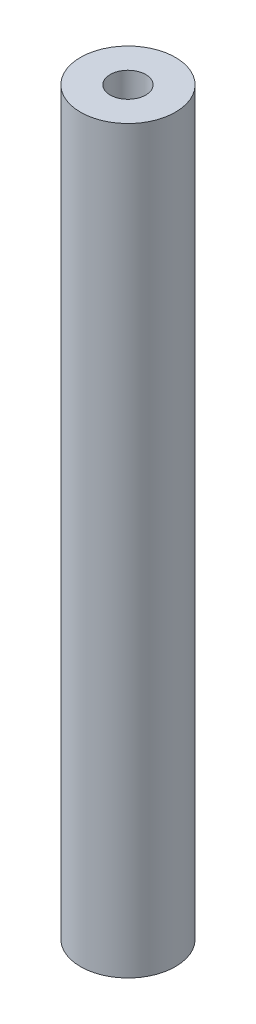
SolidWorks part; units mm, degrees
material "Aleación 6061"
ref_plane "Alzado" through (0, 0, 0) normal (0, 0, 1) x (1, 0, 0)
ref_plane "Planta" through (0, 0, 0) normal (0, 1, 0) x (1, 0, 0)
ref_plane "Vista lateral" through (0, 0, 0) normal (1, 0, 0) x (0, 0, -1)
sketch "Sk_Tubo" plane through (0, 0, 0) normal (0, 1, 0) x (1, 0, 0)
  circle A0 centre (0, -250) radius 6
  circle A1 centre (0, -250) radius 2.25
  dimension "D1" = 12
  dimension "D3" = 4.5
  dimension "D2" = 250
  dimension "D4" = 250
extrude "Tubo" add sketch "Sk_Tubo" along normal blind 93.5 from offset 46.75
